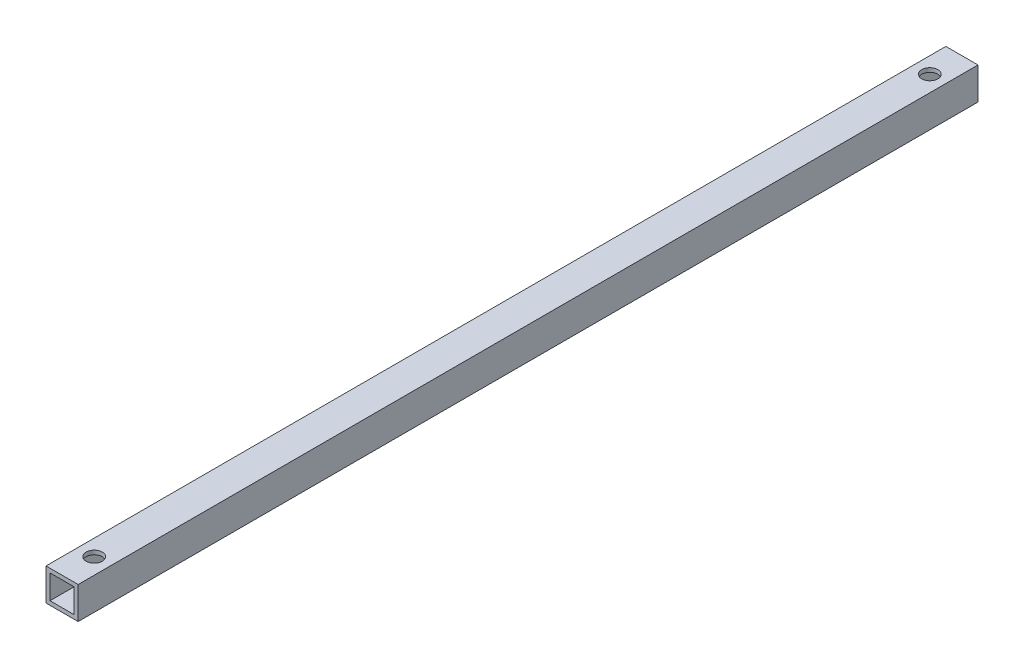
SolidWorks part; units mm, degrees
material "6061-T6 (SS)"
ref_plane "Front Plane" through (0, 0, 0) normal (0, 0, 1) x (1, 0, 0)
ref_plane "Top Plane" through (0, 0, 0) normal (0, 1, 0) x (1, 0, 0)
ref_plane "Right Plane" through (0, 0, 0) normal (1, 0, 0) x (0, 0, -1)
sketch "Sketch1" plane through (0, 0, 0) normal (0, 0, 1) x (1, 0, 0)
  line L0 (342.9, 66.675) -> (317.5, 66.675) construction
  line L1 (317.5, 92.075) -> (317.5, 66.675) construction
  line L2 (342.9, 92.075) -> (317.5, 92.075) construction
  line L3 (342.9, 92.075) -> (342.9, 66.675) construction
  line L4 (342.9, 66.675) -> (317.5, 66.675)
  line L5 (317.5, 92.075) -> (317.5, 66.675)
  line L6 (342.9, 92.075) -> (317.5, 92.075)
  line L7 (342.9, 92.075) -> (342.9, 66.675)
  line L8 (339.725, 88.9) -> (320.675, 88.9)
  line L9 (320.675, 88.9) -> (320.675, 69.85)
  line L10 (339.725, 69.85) -> (320.675, 69.85)
  line L11 (339.725, 88.9) -> (339.725, 69.85)
  dimension "D1" = 3.175
extrude "Boss-Extrude1" add sketch "Sketch1" along normal up to vertex (355.6 mm away) and the other way up to vertex (355.6 mm away)
sketch "Sketch2" plane through (0, 92.075, 0) normal (0, 1, 0) x (1, 0, 0)
  line L0 (330.2, 355.6) -> (330.2, 330.2) construction
  line L1 (342.9, 355.6) -> (317.5, 355.6) construction
  line L2 (330.2, 330.2) -> (330.2, -330.2) construction
  line L3 (330.2, -330.2) -> (330.2, -355.6) construction
  line L4 (342.9, -355.6) -> (317.5, -355.6) construction
  circle A0 centre (330.2, -330.2) radius 6.35
  circle A1 centre (330.2, 330.2) radius 6.35
  dimension "D1" = 12.7
  dimension "D2" = 25.4
extrude "Cut-Extrude1" cut sketch "Sketch2" against normal through all
